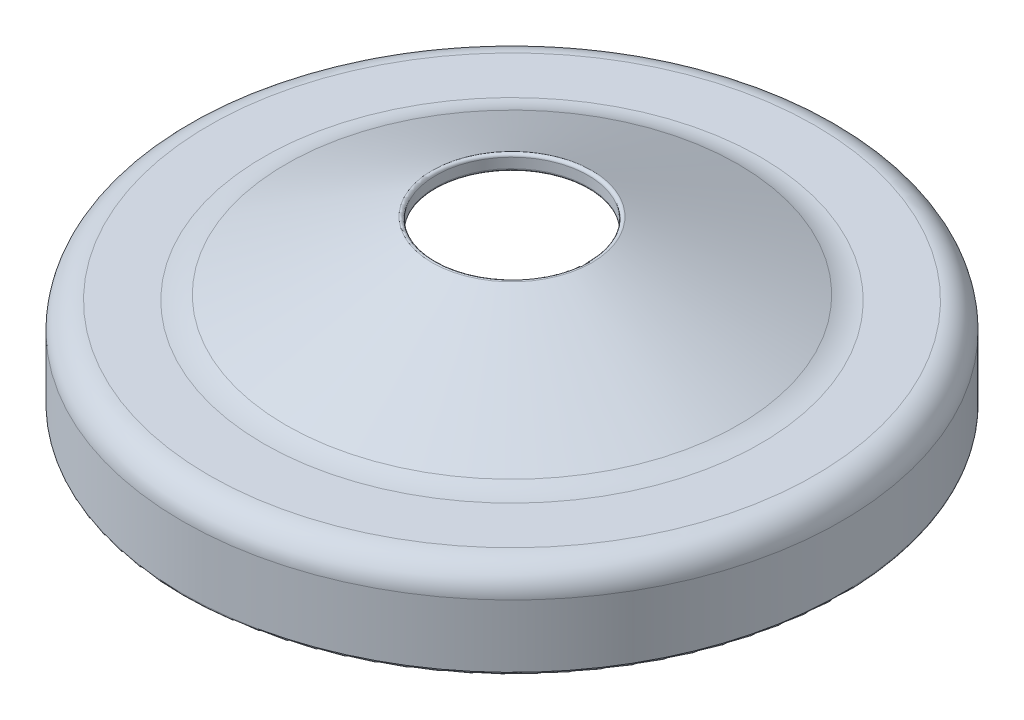
SolidWorks part; units mm, degrees
ref_plane "Front Plane" through (0, 0, 0) normal (0, 0, 1) x (1, 0, 0)
ref_plane "Top Plane" through (0, 0, 0) normal (0, 1, 0) x (1, 0, 0)
ref_plane "Right Plane" through (0, 0, 0) normal (1, 0, 0) x (0, 0, -1)
sketch "Sketch1" plane through (0, 0, 0) normal (0, 0, 1) x (1, 0, 0)
  line L0 (0, 0) -> (0, 40.9071) construction
  line L1 (-14.35, 0) -> (-44.6, -14)
  line L2 (-44.6, -14) -> (-62.1, -14)
  line L3 (-62.1, -14) -> (-62.1, -31.3)
  line L4 (-14.35, -2.9751) -> (-44.0055, -16.7)
  line L5 (-44.0055, -16.7) -> (-59.4, -16.7)
  line L6 (-59.4, -16.7) -> (-59.4, -31.3)
  line L7 (-62.1, -31.3) -> (-59.4, -31.3)
  line L8 (-14.35, 0) -> (-14.35, -2.9751)
  line L9 (-13.216, -2.4503) -> (-44.0055, -16.7) construction
  dimension "D1" = 17.3
  dimension "D2" = 31.3
  dimension "D3" = 124.2
  dimension "D4" = 17.5
  dimension "D5" = 28.7
  dimension "D6" = 2.7
revolve "Revolve1" add sketch "Sketch1" angle 360 about L0
fillet "Fillet1" radius 5 1 edges at (0, -14, -62.1)
fillet "Fillet2" radius 2.3 1 edges at (0, -16.7, -59.4)
fillet "Fillet3" radius 10 1 edges at (0, -14, -44.6)
fillet "Fillet4" radius 12.7 1 edges at (0, -16.7, -44.0055)
fillet "Fillet5" radius 0.5 4 edges at (0, -2.9751, -14.35) (0, 0, -14.35) (0, -31.3, -62.1) (0, -31.3, -59.4)
